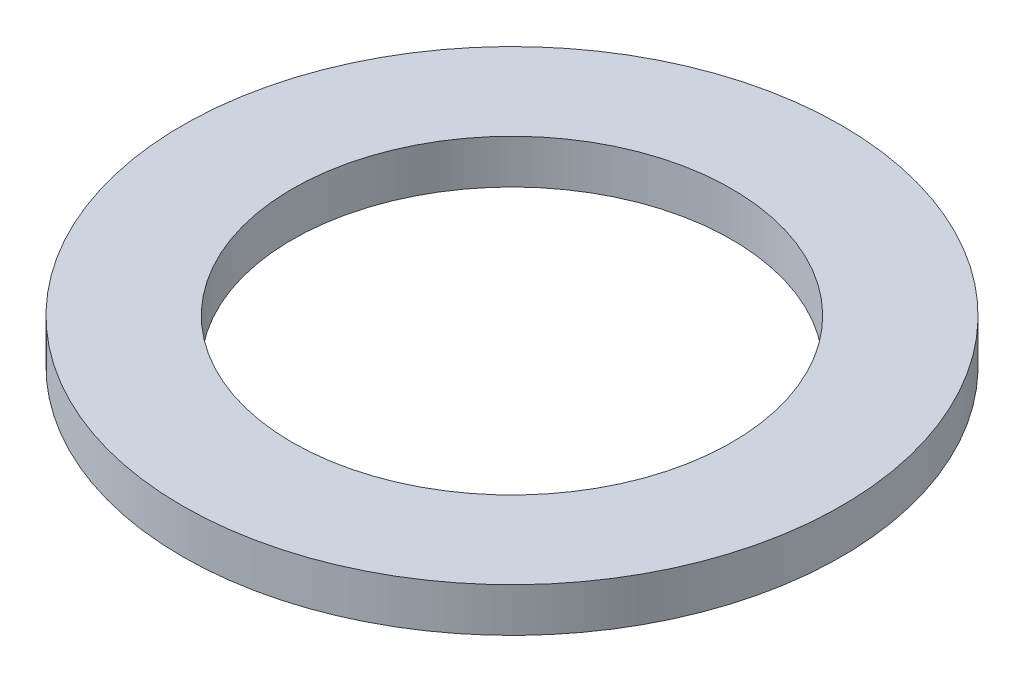
SolidWorks part; units mm, degrees
ref_plane "Front Plane" through (0, 0, 0) normal (0, 0, 1) x (1, 0, 0)
ref_plane "Top Plane" through (0, 0, 0) normal (0, 1, 0) x (1, 0, 0)
ref_plane "Right Plane" through (0, 0, 0) normal (1, 0, 0) x (0, 0, -1)
sketch "Sketch1" plane through (0, 0, 0) normal (0, 1, 0) x (1, 0, 0)
  line L0 (-4.7625, 0) -> (4.7625, 0) construction
  line L1 (-3.175, 0) -> (3.175, 0) construction
  point P4 (0, 0)
  point P7 (0, 0)
  dimension "OD" = 9.525
  dimension "ID" = 6.35
sketch "Sketch2" plane through (0, 0, 0) normal (0, 0, 1) x (1, 0, 0)
  line L0 (4.7625, -0.3175) -> (4.7625, 0.3175) construction
  point P4 (4.7625, 0)
  dimension "Thickness" = 0.635
sketch "Sketch3" plane through (0, 0, 0) normal (0, 1, 0) x (1, 0, 0)
  circle A0 centre (0, 0) radius 4.7625
  circle A1 centre (0, 0) radius 3.175
extrude "Boss-Extrude1" add sketch "Sketch3" against normal up to vertex (0.3175 mm away) and the other way up to vertex (0.3175 mm away)
